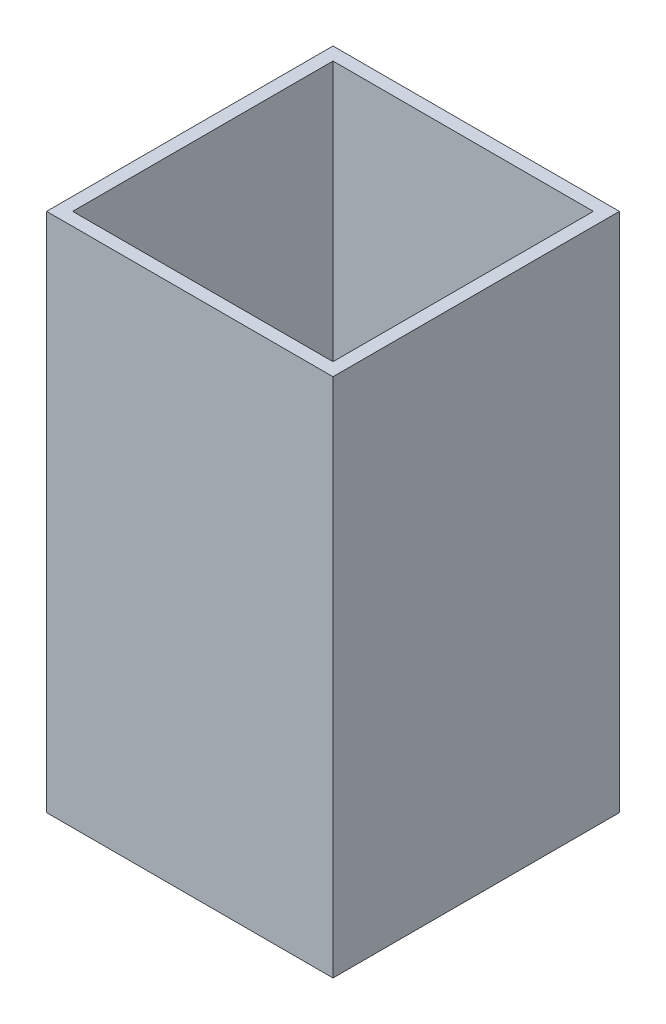
SolidWorks part; units mm, degrees
ref_plane "前视基准面" through (0, 0, 0) normal (0, 0, 1) x (1, 0, 0)
ref_plane "上视基准面" through (0, 0, 0) normal (0, 1, 0) x (1, 0, 0)
ref_plane "右视基准面" through (0, 0, 0) normal (1, 0, 0) x (0, 0, -1)
sketch "草图1" plane through (0, 0, 0) normal (0, 1, 0) x (1, 0, 0)
  line L1 (-27.5, 27.5) -> (27.5, 27.5)
  line L2 (-27.5, 27.5) -> (-27.5, -27.5)
  line L3 (-27.5, -27.5) -> (27.5, -27.5)
  line L4 (27.5, 27.5) -> (27.5, -27.5)
  line L5 (-27.5, 27.5) -> (27.5, -27.5) construction
  line L6 (-27.5, -27.5) -> (27.5, 27.5) construction
  point P0 (0, 0)
  dimension "D1" = 55
extrude "凸台-拉伸1" add sketch "草图1" along normal blind 100 contours L3 L4 L1 L2
sketch "草图2" plane through (0, 0, 0) normal (0, 1, 0) x (1, 0, 0)
  line L1 (-25, 25) -> (25, 25)
  line L2 (-25, 25) -> (-25, -25)
  line L3 (-25, -25) -> (25, -25)
  line L4 (25, 25) -> (25, -25)
  line L5 (-25, 25) -> (25, -25) construction
  line L6 (-25, -25) -> (25, 25) construction
  point P0 (0, 0)
  dimension "D1" = 50
  dimension "D2" = 50
extrude "切除-拉伸1" cut sketch "草图2" against normal through all and the other way through all
